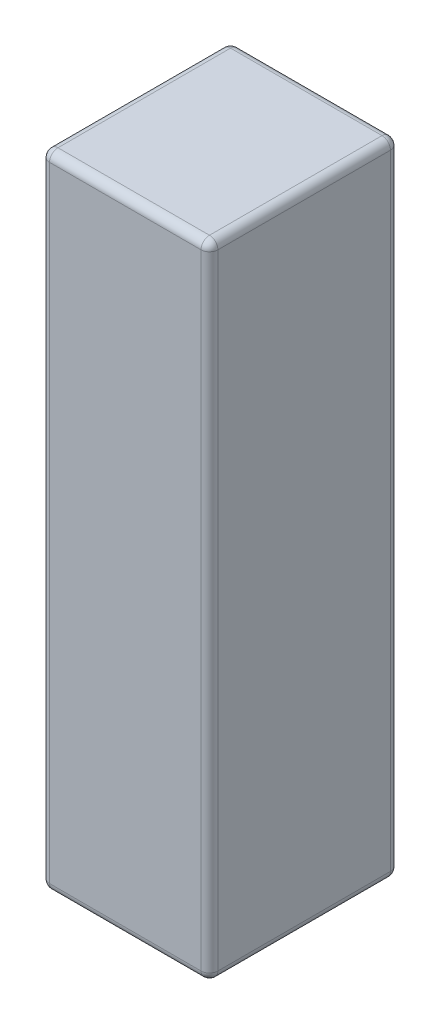
SolidWorks part; units mm, degrees
ref_plane "Front Plane" through (0, 0, 0) normal (0, 0, 1) x (1, 0, 0)
ref_plane "Top Plane" through (0, 0, 0) normal (0, 1, 0) x (1, 0, 0)
ref_plane "Right Plane" through (0, 0, 0) normal (1, 0, 0) x (0, 0, -1)
sketch "Sketch1" plane through (0, 0, 0) normal (0, 1, 0) x (1, 0, 0)
  line L1 (20, 22.5) -> (-20, 22.5)
  line L2 (20, 22.5) -> (20, -22.5)
  line L3 (20, -22.5) -> (-20, -22.5)
  line L4 (-20, 22.5) -> (-20, -22.5)
  line L5 (20, 22.5) -> (-20, -22.5) construction
  line L6 (20, -22.5) -> (-20, 22.5) construction
  point P0 (0, 0)
  dimension "D1" = 45
  dimension "D2" = 40
extrude "Boss-Extrude1" add sketch "Sketch1" along normal blind 152.4
fillet "Fillet1" radius 2 12 edges at (-20, 0, 0) (-20, 76.2, -22.5) (0, 0, -22.5) (20, 76.2, -22.5) (20, 0, 0) (0, 152.4, -22.5) (20, 152.4, 0) (-20, 152.4, 0) (-20, 76.2, 22.5) (0, 152.4, 22.5) (20, 76.2, 22.5) (0, 0, 22.5)
